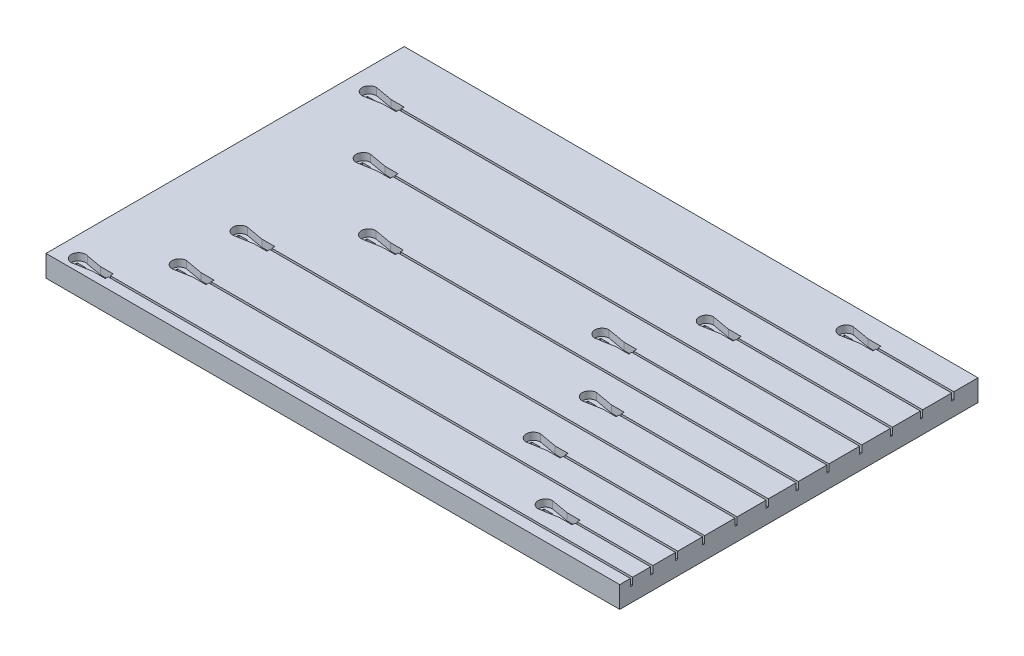
SolidWorks part; units mm, degrees
ref_plane "Front Plane" through (0, 0, 0) normal (0, 0, 1) x (1, 0, 0)
ref_plane "Top Plane" through (0, 0, 0) normal (0, 1, 0) x (1, 0, 0)
ref_plane "Right Plane" through (0, 0, 0) normal (1, 0, 0) x (0, 0, -1)
sketch "Sketch1" plane through (0, 0, 0) normal (0, 1, 0) x (1, 0, 0)
  line L1 (-400.05, 249.809) -> (400.05, 249.809)
  line L2 (-400.05, 249.809) -> (-400.05, -249.809)
  line L3 (-400.05, -249.809) -> (400.05, -249.809)
  line L4 (400.05, 249.809) -> (400.05, -249.809)
  line L5 (-400.05, 249.809) -> (400.05, -249.809) construction
  line L6 (-400.05, -249.809) -> (400.05, 249.809) construction
  point P0 (0, 0)
  dimension "D1" = 800.1
  dimension "D2" = 499.618
extrude "Boss-Extrude1" add sketch "Sketch1" against normal blind 30
sketch "Sketch2" plane through (0, 0, 0) normal (0, 1, 0) x (1, 0, 0)
  line L0 (251.3667, 224.5827) -> (276.2587, 220.1707)
  line L1 (251.3667, 214.5827) -> (400.05, 214.5827) construction
  line L2 (400.05, -249.809) -> (400.05, 249.809) construction
  line L3 (276.2587, 220.1707) -> (294.2419, 220.1707)
  line L4 (294.2419, 213.0827) -> (400.05, 213.0827)
  line L6 (294.2419, 220.1707) -> (294.2419, 216.0827)
  line L7 (294.2419, 216.0827) -> (400.05, 216.0827)
  line L8 (294.2419, 208.9947) -> (294.2419, 213.0827)
  line L9 (276.2587, 208.9947) -> (294.2419, 208.9947)
  line L10 (251.3667, 204.5827) -> (276.2587, 208.9947)
  line L11 (-369.9453, 181.0407) -> (-345.0533, 176.6287)
  line L12 (-369.9453, 171.0407) -> (-96.802, 171.0407) construction
  line L13 (-345.0533, 176.6287) -> (-327.0701, 176.6287)
  line L14 (-327.0701, 178.1738) -> (-327.0701, 177.7206)
  line L15 (-279.358, 172.5407) -> (-279.358, 169.5407)
  line L16 (-327.0701, 176.6287) -> (-327.0701, 178.1738)
  line L17 (-327.0701, 176.6287) -> (-327.0701, 172.5407)
  line L18 (-327.0701, 165.4527) -> (-327.0701, 163.9076)
  line L19 (-345.0533, 165.4527) -> (-327.0701, 165.4527)
  line L20 (-369.9453, 161.0407) -> (-345.0533, 165.4527)
  line L21 (-327.0701, 165.4527) -> (-327.0701, 164.3609)
  line L22 (-327.0701, 165.4527) -> (-327.0701, 169.5407)
  line L23 (-327.0701, 172.5407) -> (400.05, 172.5407)
  line L24 (-327.0701, 169.5407) -> (400.05, 169.5407)
  line L25 (142.1169, 138.9838) -> (167.0089, 134.5718)
  line L26 (142.1169, 128.9838) -> (400.05, 128.9838) construction
  line L27 (167.0089, 134.5718) -> (184.9921, 134.5718)
  line L28 (184.9921, 127.4838) -> (400.05, 127.4838)
  line L29 (197.3736, 130.4838) -> (197.3736, 127.4838)
  line L30 (184.9921, 134.5718) -> (184.9921, 130.4838)
  line L31 (184.9921, 130.4838) -> (400.05, 130.4838)
  line L32 (184.9921, 123.3958) -> (184.9921, 127.4838)
  line L33 (167.0089, 123.3958) -> (184.9921, 123.3958)
  line L34 (142.1169, 118.9838) -> (167.0089, 123.3958)
  line L35 (-293.5798, 96.2261) -> (-268.6878, 91.8141)
  line L36 (-293.5798, 86.2261) -> (-20.4365, 86.2261) construction
  line L37 (-268.6878, 91.8141) -> (-250.7046, 91.8141)
  line L38 (-250.7046, 93.3593) -> (-250.7046, 92.906)
  line L40 (-250.7046, 91.8141) -> (-250.7046, 93.3593)
  line L41 (-250.7046, 91.8141) -> (-250.7046, 87.7261)
  line L42 (-250.7046, 80.6381) -> (-250.7046, 79.093)
  line L43 (-268.6878, 80.6381) -> (-250.7046, 80.6381)
  line L44 (-293.5798, 76.2261) -> (-268.6878, 80.6381)
  line L45 (-250.7046, 80.6381) -> (-250.7046, 79.5463)
  line L46 (-250.7046, 80.6381) -> (-250.7046, 84.7261)
  line L47 (-250.7046, 87.7261) -> (400.05, 87.7261)
  line L48 (-250.7046, 84.7261) -> (400.05, 84.7261)
  line L49 (85.0051, 50.4811) -> (109.8971, 46.0691)
  line L50 (85.0051, 40.4811) -> (312.4284, 40.4811) construction
  line L51 (109.8971, 46.0691) -> (127.8803, 46.0691)
  line L52 (127.8803, 39.0823) -> (400.05, 39.0823)
  line L54 (127.8803, 46.0691) -> (127.8803, 41.8798)
  line L55 (127.8803, 41.8798) -> (400.05, 41.8798)
  line L56 (127.8803, 34.8931) -> (127.8803, 39.0823)
  line L57 (109.8971, 34.8931) -> (127.8803, 34.8931)
  line L58 (85.0051, 30.4811) -> (109.8971, 34.8931)
  line L59 (72.4365, 249.809) -> (72.4365, -249.809) construction
  line L60 (400.05, 249.809) -> (-400.05, 249.809) construction
  line L61 (-400.05, -249.809) -> (400.05, -249.809) construction
  line L62 (-72.4365, 249.809) -> (72.4365, 249.809)
  line L63 (-72.4365, 249.809) -> (-72.4365, -249.809) construction
  line L64 (-197.6814, 7.7188) -> (-172.7894, 3.3068)
  line L65 (-197.6814, -2.2812) -> (75.4619, -2.2812) construction
  line L66 (-172.7894, 3.3068) -> (-154.8062, 3.3068)
  line L67 (-154.8062, 4.8519) -> (-154.8062, 4.3987)
  line L69 (-154.8062, 3.3068) -> (-154.8062, 4.8519)
  line L70 (-154.8062, 3.3068) -> (-154.8062, -0.7812)
  line L71 (-154.8062, -7.8692) -> (-154.8062, -9.4143)
  line L72 (-172.7894, -7.8692) -> (-154.8062, -7.8692)
  line L73 (-197.6814, -12.2812) -> (-172.7894, -7.8692)
  line L74 (-154.8062, -7.8692) -> (-154.8062, -8.9611)
  line L75 (-154.8062, -7.8692) -> (-154.8062, -3.7812)
  line L76 (-154.8062, -0.7812) -> (400.05, -0.7812)
  line L77 (-154.8062, -3.7812) -> (400.05, -3.7812)
  line L78 (151.9583, -34.0236) -> (176.8503, -38.4356)
  line L79 (151.9583, -44.0236) -> (400.05, -44.0236) construction
  line L80 (176.8503, -38.4356) -> (194.8335, -38.4356)
  line L81 (194.8335, -45.5236) -> (400.05, -45.5236)
  line L83 (194.8335, -38.4356) -> (194.8335, -42.5236)
  line L84 (194.8335, -42.5236) -> (400.05, -42.5236)
  line L85 (194.8335, -49.6116) -> (194.8335, -45.5236)
  line L86 (176.8503, -49.6116) -> (194.8335, -49.6116)
  line L87 (151.9583, -54.0236) -> (176.8503, -49.6116)
  line L88 (-291.5784, -77.59) -> (-266.6864, -82.002)
  line L89 (-291.5784, -87.59) -> (-18.4351, -87.59) construction
  line L90 (-266.6864, -82.002) -> (-248.7032, -82.002)
  line L91 (-248.7032, -80.4569) -> (-248.7032, -80.9102)
  line L93 (-248.7032, -82.002) -> (-248.7032, -80.4569)
  line L94 (-248.7032, -82.002) -> (-248.7032, -86.09)
  line L95 (-248.7032, -93.178) -> (-248.7032, -94.7231)
  line L96 (-266.6864, -93.178) -> (-248.7032, -93.178)
  line L97 (-291.5784, -97.59) -> (-266.6864, -93.178)
  line L98 (-248.7032, -93.178) -> (-248.7032, -94.2699)
  line L99 (-248.7032, -93.178) -> (-248.7032, -89.09)
  line L100 (-248.7032, -86.09) -> (400.05, -86.09)
  line L101 (-248.7032, -89.09) -> (400.05, -89.09)
  line L102 (-293.4691, -160.4701) -> (-268.5771, -164.8821)
  line L103 (-293.4691, -170.4701) -> (-20.3258, -170.4701) construction
  line L104 (-268.5771, -164.8821) -> (-250.5939, -164.8821)
  line L105 (-250.5939, -163.337) -> (-250.5939, -163.7902)
  line L107 (-250.5939, -164.8821) -> (-250.5939, -163.337)
  line L108 (-250.5939, -164.8821) -> (-250.5939, -168.9701)
  line L109 (-250.5939, -176.0581) -> (-250.5939, -177.6032)
  line L110 (-268.5771, -176.0581) -> (-250.5939, -176.0581)
  line L111 (-293.4691, -180.4701) -> (-268.5771, -176.0581)
  line L112 (-250.5939, -176.0581) -> (-250.5939, -177.1499)
  line L113 (-250.5939, -176.0581) -> (-250.5939, -171.9701)
  line L114 (-250.5939, -168.9701) -> (400.05, -168.9701)
  line L115 (-250.5939, -171.9701) -> (400.05, -171.9701)
  line L116 (-371.1894, -223.3399) -> (-346.2974, -227.7519)
  line L117 (-371.1894, -233.3399) -> (-98.0462, -233.3399) construction
  line L118 (-346.2974, -227.7519) -> (-328.3142, -227.7519)
  line L119 (-328.3142, -226.2068) -> (-328.3142, -226.66)
  line L121 (-328.3142, -227.7519) -> (-328.3142, -226.2068)
  line L122 (-328.3142, -227.7519) -> (-328.3142, -231.8399)
  line L123 (-328.3142, -238.9279) -> (-328.3142, -240.473)
  line L124 (-346.2974, -238.9279) -> (-328.3142, -238.9279)
  line L125 (-371.1894, -243.3399) -> (-346.2974, -238.9279)
  line L126 (-328.3142, -238.9279) -> (-328.3142, -240.0198)
  line L127 (-328.3142, -238.9279) -> (-328.3142, -234.8399)
  line L128 (-328.3142, -231.8399) -> (400.05, -231.8399)
  line L129 (-328.3142, -234.8399) -> (400.05, -234.8399)
  line L130 (162.656, -122.8982) -> (187.548, -127.3102)
  line L131 (162.656, -132.8982) -> (400.05, -132.8982) construction
  line L132 (187.548, -127.3102) -> (205.5312, -127.3102)
  line L133 (205.5312, -134.3982) -> (400.05, -134.3982)
  line L135 (205.5312, -127.3102) -> (205.5312, -131.3982)
  line L136 (205.5312, -131.3982) -> (400.05, -131.3982)
  line L137 (205.5312, -138.4862) -> (205.5312, -134.3982)
  line L138 (187.548, -138.4862) -> (205.5312, -138.4862)
  line L139 (162.656, -142.8982) -> (187.548, -138.4862)
  line L140 (251.6853, -195.226) -> (276.5773, -199.638)
  line L141 (251.6853, -205.226) -> (400.05, -205.226) construction
  line L142 (276.5773, -199.638) -> (294.5605, -199.638)
  line L143 (294.5605, -206.726) -> (400.05, -206.726)
  line L145 (294.5605, -199.638) -> (294.5605, -203.726)
  line L146 (294.5605, -203.726) -> (400.05, -203.726)
  line L147 (294.5605, -210.814) -> (294.5605, -206.726)
  line L148 (276.5773, -210.814) -> (294.5605, -210.814)
  line L149 (251.6853, -215.226) -> (276.5773, -210.814)
  line L151 (246.0298, 217.1077) -> (256.7036, 217.1077)
  line L152 (246.0298, 217.1077) -> (246.0298, 212.0577)
  line L153 (246.0298, 212.0577) -> (256.7036, 212.0577)
  line L154 (256.7036, 217.1077) -> (256.7036, 212.0577)
  line L155 (246.0298, 217.1077) -> (256.7036, 212.0577) construction
  line L156 (246.0298, 212.0577) -> (256.7036, 217.1077) construction
  line L160 (-375.4776, 174.0062) -> (-364.8038, 174.0062)
  line L161 (-375.4776, 174.0062) -> (-375.4776, 168.9562)
  line L162 (-375.4776, 168.9562) -> (-364.8038, 168.9562)
  line L163 (-364.8038, 174.0062) -> (-364.8038, 168.9562)
  line L164 (136.5299, 131.8566) -> (147.2038, 131.8566)
  line L165 (136.5299, 131.8566) -> (136.5299, 126.8066)
  line L166 (136.5299, 126.8066) -> (147.2038, 126.8066)
  line L167 (147.2038, 131.8566) -> (147.2038, 126.8066)
  line L168 (-299.2613, 89.3297) -> (-288.5874, 89.3297)
  line L169 (-299.2613, 89.3297) -> (-299.2613, 84.2798)
  line L170 (-299.2613, 84.2798) -> (-288.5874, 84.2798)
  line L171 (-288.5874, 89.3297) -> (-288.5874, 84.2798)
  line L172 (-202.6709, 0.9962) -> (-191.997, 0.9962)
  line L173 (-202.6709, 0.9962) -> (-202.6709, -4.0537)
  line L174 (-202.6709, -4.0537) -> (-191.997, -4.0537)
  line L175 (-191.997, 0.9962) -> (-191.997, -4.0537)
  line L176 (-297.1417, -84.615) -> (-286.4678, -84.615)
  line L177 (-297.1417, -84.615) -> (-297.1417, -89.6649)
  line L178 (-297.1417, -89.6649) -> (-286.4678, -89.6649)
  line L179 (-286.4678, -84.615) -> (-286.4678, -89.6649)
  line L180 (-299.1015, -167.6424) -> (-288.4276, -167.6424)
  line L181 (-299.1015, -167.6424) -> (-299.1015, -172.6924)
  line L182 (-299.1015, -172.6924) -> (-288.4276, -172.6924)
  line L183 (-288.4276, -167.6424) -> (-288.4276, -172.6924)
  line L184 (-376.9133, -231.0001) -> (-366.2395, -231.0001)
  line L185 (-376.9133, -231.0001) -> (-376.9133, -236.0501)
  line L186 (-376.9133, -236.0501) -> (-366.2395, -236.0501)
  line L187 (-366.2395, -231.0001) -> (-366.2395, -236.0501)
  line L188 (245.966, -202.3989) -> (256.6398, -202.3989)
  line L189 (245.966, -202.3989) -> (245.966, -207.4489)
  line L190 (245.966, -207.4489) -> (256.6398, -207.4489)
  line L191 (256.6398, -202.3989) -> (256.6398, -207.4489)
  line L192 (157.1887, -129.9705) -> (167.8626, -129.9705)
  line L193 (157.1887, -129.9705) -> (157.1887, -135.0205)
  line L194 (157.1887, -135.0205) -> (167.8626, -135.0205)
  line L195 (167.8626, -129.9705) -> (167.8626, -135.0205)
  line L196 (146.6996, -41.0802) -> (157.3735, -41.0802)
  line L197 (146.6996, -41.0802) -> (146.6996, -46.1302)
  line L198 (146.6996, -46.1302) -> (157.3735, -46.1302)
  line L199 (157.3735, -41.0802) -> (157.3735, -46.1302)
  line L200 (79.4858, 42.8163) -> (90.1596, 42.8163)
  line L201 (79.4858, 42.8163) -> (79.4858, 37.7663)
  line L202 (79.4858, 37.7663) -> (90.1596, 37.7663)
  line L203 (90.1596, 42.8163) -> (90.1596, 37.7663)
  line L204 (240.9019, 249.809) -> (240.9019, -249.809) construction
  line L205 (400.05, 216.0827) -> (400.05, 213.0827)
  line L206 (400.05, 130.4838) -> (400.05, 127.4838)
  line L208 (-381.1039, 249.809) -> (-381.1039, -249.809) construction
  line L209 (400.05, 172.5407) -> (400.05, 169.5407)
  line L210 (400.05, 130.4838) -> (400.05, 127.4838)
  line L211 (400.05, 87.7261) -> (400.05, 84.7261)
  line L212 (400.05, 41.8798) -> (400.05, 39.0823)
  line L213 (400.05, 0) -> (400.05, -3.7812)
  line L214 (400.05, -42.5236) -> (400.05, -45.5236)
  line L215 (400.05, -86.09) -> (400.05, -89.09)
  line L216 (400.05, -131.3982) -> (400.05, -134.3982)
  line L217 (400.05, -168.9448) -> (400.05, -171.9701)
  line L218 (400.05, -203.726) -> (400.05, -206.726)
  line L219 (400.05, -231.8399) -> (400.05, -234.8399)
  circle A0 centre (251.3667, 214.5827) radius 10
  circle A1 centre (-369.9453, 171.0407) radius 10
  circle A2 centre (142.1169, 128.9838) radius 10
  circle A3 centre (-293.5798, 86.2261) radius 10
  circle A4 centre (85.0051, 40.4811) radius 10
  circle A5 centre (-197.6814, -2.2812) radius 10
  circle A6 centre (151.9583, -44.0236) radius 10
  circle A7 centre (-291.5784, -87.59) radius 10
  circle A8 centre (-293.4691, -170.4701) radius 10
  circle A9 centre (-371.1894, -233.3399) radius 10
  circle A10 centre (162.656, -132.8982) radius 10
  circle A11 centre (251.6853, -205.226) radius 10
  point P28 (-279.358, 171.0407)
  point P48 (197.3736, 128.9838)
  point P94 (148.0316, 38.7544)
  point P185 (-280.6021, -233.3399)
  point P251 (0, 249.809)
  line M22 (400.05, -249.809) -> (400.05, 249.809)
  dimension "D1" = 20
  dimension "D2" = 24.892
  dimension "D3" = 17.9832
  dimension "D4" = 24.892
  dimension "D5" = 17.9832
extrude "Cut-Extrude3" cut sketch "Sketch2" against normal blind 10 contours L10 A0 L0 L151 L154 L153 L152 | A0 L10 L9 L8 L4 L7 L6 L3 L0 M22 | L15 L24 L23 M22 | A1 L20 L19 L22 L24 L15 L23 L17 L13 L11 | L20 A1 L11 L160 L163 L162 L161 | L34 A2 L25 L164 L167 L166 L165 | A2 L34 L33 L32 L28 L29 L31 L30 L27 L25 | L31 L29 L28 M22 | L44 A3 L35 L168 L171 L170 L169 | A3 L44 L43 L46 L48 L47 L41 L37 L35 M22 | L58 A4 L49 L200 L203 L202 L201 | L203 L200 L201 L202 | A4 L58 L57 L56 L52 L55 L54 L51 L49 M22 | L73 A5 L64 L172 L175 L174 L173 | A5 L73 L72 L75 L77 L76 L70 L66 L64 M22 | L97 A7 L88 L176 L179 L178 L177 | A7 L97 L96 L99 L101 L100 L94 L90 L88 M22 | L87 A6 L78 L196 L199 L198 L197 | A6 L87 L86 L85 L81 L84 L83 L80 L78 M22 | L111 A8 L102 L180 L183 L182 L181 | A8 L111 L110 L113 L115 L114 L108 L104 L102 M22 | L139 A10 L130 L192 L195 L194 L193 | A10 L139 L138 L137 L133 L136 L135 L132 L130 M22 | L149 A11 L140 L188 L191 L190 L189 | A11 L149 L148 L147 L143 L146 L145 L142 L140 M22 | L125 A9 L116 L184 L187 L186 L185 | A9 L125 L124 L127 L129 L128 L122 L118 L116 M22 | L154 L151 L152 L153 | L163 L160 L161 L162 | L167 L164 L165 L166 | L171 L168 L169 L170 | L175 L172 L173 L174 | L199 L196 L197 L198 | L179 L176 L177 L178 | L195 L192 L193 L194 | L183 L180 L181 L182 | L191 L188 L189 L190 | L187 L184 L185 L186
sketch "Sketch3" plane through (0, -10, 0) normal (0, 1, 0) x (1, 0, 0)
  line L1 (245.4144, 218.3712) -> (257.319, 218.3712)
  line L2 (245.4144, 218.3712) -> (245.4144, 210.7942)
  line L3 (245.4144, 210.7942) -> (257.319, 210.7942)
  line L4 (257.319, 218.3712) -> (257.319, 210.7942)
  line L5 (245.4144, 218.3712) -> (257.319, 210.7942) construction
  line L6 (245.4144, 210.7942) -> (257.319, 218.3712) construction
  line L11 (-375.3339, 173.8587) -> (-364.2125, 173.8587)
  line L12 (-375.3339, 173.8587) -> (-375.3339, 166.7624)
  line L13 (-375.3339, 166.7624) -> (-364.2125, 166.7624)
  line L14 (-364.2125, 173.8587) -> (-364.2125, 166.7624)
  line L27 (145.9709, -40.2518) -> (157.8754, -40.2518)
  line L28 (79.0862, 44.3656) -> (90.9907, 44.3656)
  line L29 (79.0862, 44.3656) -> (79.0862, 36.7886)
  line L30 (79.0862, 36.7886) -> (90.9907, 36.7886)
  line L31 (90.9907, 44.3656) -> (90.9907, 36.7886)
  line L32 (145.9709, -40.2518) -> (145.9709, -47.8288)
  line L33 (-203.6796, 1.6086) -> (-191.7751, 1.6086)
  line L34 (-203.6796, 1.6086) -> (-203.6796, -5.9684)
  line L35 (-203.6796, -5.9684) -> (-191.7751, -5.9684)
  line L36 (-191.7751, 1.6086) -> (-191.7751, -5.9684)
  line L37 (145.9709, -47.8288) -> (157.8754, -47.8288)
  line L38 (157.8754, -40.2518) -> (157.8754, -47.8288)
  line L39 (-297.7034, -83.1822) -> (-285.7989, -83.1822)
  line L40 (-297.7034, -83.1822) -> (-297.7034, -90.7593)
  line L41 (-297.7034, -90.7593) -> (-285.7989, -90.7593)
  line L42 (-285.7989, -83.1822) -> (-285.7989, -90.7593)
  line L51 (-376.9586, -229.437) -> (-365.054, -229.437)
  line L52 (-376.9586, -229.437) -> (-376.9586, -237.0141)
  line L53 (-376.9586, -237.0141) -> (-365.054, -237.0141)
  line L54 (-365.054, -229.437) -> (-365.054, -237.0141)
  line L55 (245.7811, -201.2349) -> (257.6856, -201.2349)
  line L56 (245.7811, -201.2349) -> (245.7811, -208.812)
  line L57 (245.7811, -208.812) -> (257.6856, -208.812)
  line L58 (257.6856, -201.2349) -> (257.6856, -208.812)
  line L59 (-299.2976, 90.4809) -> (-287.393, 90.4809)
  line L60 (-299.2976, 90.4809) -> (-299.2976, 82.9038)
  line L61 (-299.2976, 82.9038) -> (-287.393, 82.9038)
  line L62 (-287.393, 90.4809) -> (-287.393, 82.9038)
  line L63 (136.158, 132.7912) -> (148.0626, 132.7912)
  line L64 (136.158, 132.7912) -> (136.158, 125.2141)
  line L65 (136.158, 125.2141) -> (148.0626, 125.2141)
  line L66 (148.0626, 132.7912) -> (148.0626, 125.2141)
  line L67 (156.4544, -128.9728) -> (168.3589, -128.9728)
  line L68 (156.4544, -128.9728) -> (156.4544, -136.5499)
  line L69 (156.4544, -136.5499) -> (168.3589, -136.5499)
  line L70 (168.3589, -128.9728) -> (168.3589, -136.5499)
  line L71 (-299.5334, -166.7397) -> (-287.6289, -166.7397)
  line L72 (-299.5334, -166.7397) -> (-299.5334, -174.3168)
  line L73 (-299.5334, -174.3168) -> (-287.6289, -174.3168)
  line L74 (-287.6289, -166.7397) -> (-287.6289, -174.3168)
  point P0 (251.3667, 214.5827)
  point P6 (0, 0)
  point P7 (0, 0)
  point P8 (0, 0)
  point P29 (0, 0)
  point P30 (0, 0)
  point P33 (0, 0)
  point P34 (0, 0)
extrude "Cut-Extrude5" cut sketch "Sketch3" against normal through all contours L14 L11 L12 L13 | L4 L1 L2 L3
